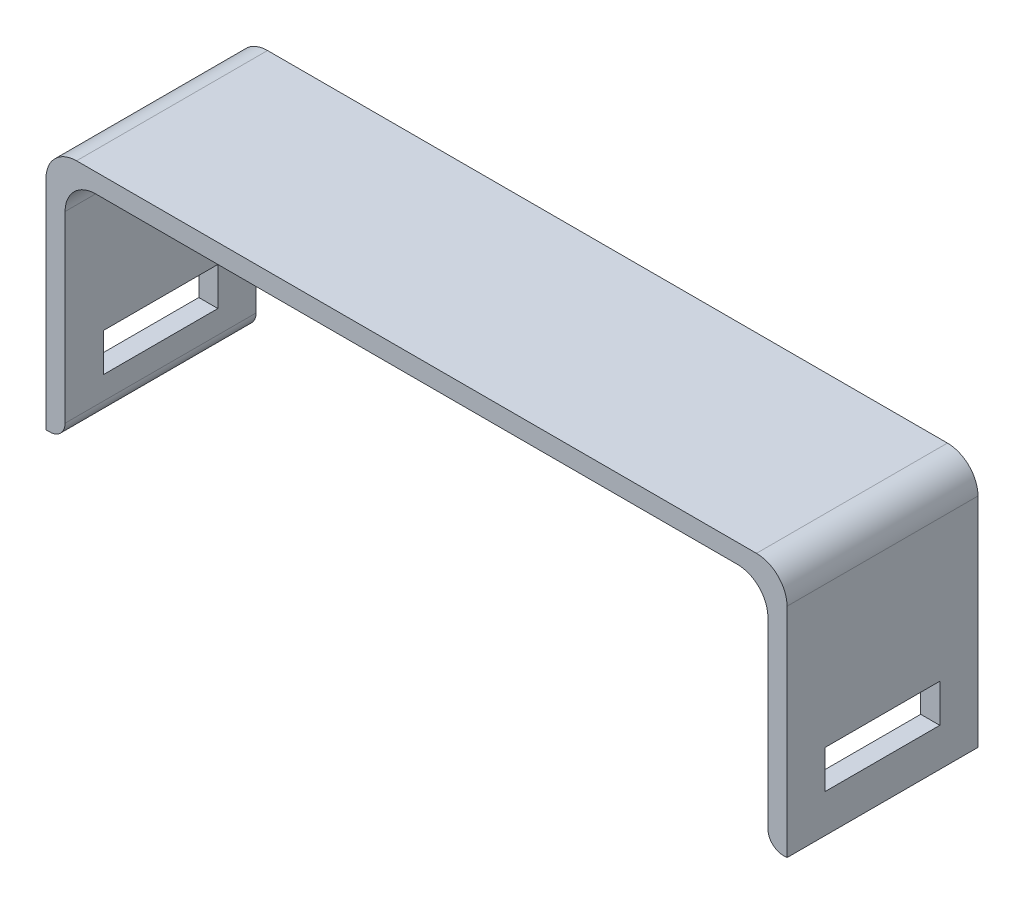
SolidWorks part; units mm, degrees
ref_plane "Front Plane" through (0, 0, 0) normal (0, 0, 1) x (1, 0, 0)
ref_plane "Top Plane" through (0, 0, 0) normal (0, 1, 0) x (1, 0, 0)
ref_plane "Right Plane" through (0, 0, 0) normal (1, 0, 0) x (0, 0, -1)
sketch "Sketch1" plane through (0, 0, 0) normal (0, 0, 1) x (1, 0, 0)
  line L0 (0, 0) -> (0, 41.275)
  line L1 (0, 41.275) -> (123.19, 41.275)
  line L2 (123.19, 41.275) -> (123.19, 0)
  line L3 (123.19, 0) -> (120.015, 0)
  line L4 (120.015, 0) -> (120.015, 38.1)
  line L5 (120.015, 38.1) -> (3.175, 38.1)
  line L6 (3.175, 38.1) -> (3.175, 0)
  line L7 (3.175, 0) -> (0, 0)
  dimension "D1" = 116.84
  dimension "D2" = 3.175
  dimension "D3" = 3.175
  dimension "D4" = 38.1
extrude "Boss-Extrude1" add sketch "Sketch1" along normal blind 31.75
sketch "Sketch2" plane through (0, 0, 0) normal (-1, 0, 0) x (0, 0, 1)
  line L0 (31.75, 0) -> (0, 0) construction
  line L1 (6.35, 12.7) -> (25.4, 12.7)
  line L2 (6.35, 12.7) -> (6.35, 6.35)
  line L3 (6.35, 6.35) -> (25.4, 6.35)
  line L4 (25.4, 12.7) -> (25.4, 6.35)
  line L5 (6.35, 12.7) -> (25.4, 6.35) construction
  line L6 (6.35, 6.35) -> (25.4, 12.7) construction
  line L7 (31.75, 38.1) -> (0, 38.1) construction
  point P0 (15.875, 9.525)
  point P8 (15.875, 0)
  dimension "D1" = 19.05
  dimension "D2" = 6.35
  dimension "D3" = 25.4
extrude "Cut-Extrude1" cut sketch "Sketch2" against normal through all
fillet "Fillet1" radius 5.08 4 edges at (120.015, 38.1, 15.875) (3.175, 38.1, 15.875) (123.19, 41.275, 15.875) (0, 41.275, 15.875)
fillet "Fillet2" radius 2.54 2 edges at (3.175, 0, 15.875) (120.015, 0, 15.875)
